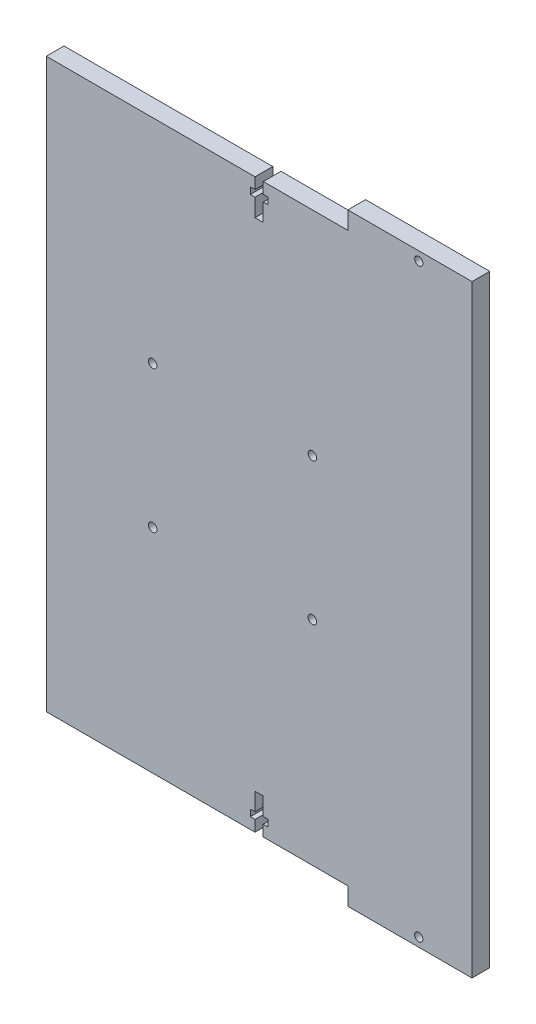
SolidWorks part; units mm, degrees
material "Acrylic (Medium-high impact)"
ref_plane "Front" through (0, 0, 0) normal (0, 0, 1) x (1, 0, 0)
ref_plane "Top" through (0, 0, 0) normal (0, 1, 0) x (1, 0, 0)
ref_plane "Right" through (0, 0, 0) normal (1, 0, 0) x (0, 0, -1)
sketch "Sketch1" plane through (0, 0, 0) normal (0, 0, 1) x (1, 0, 0)
  line L0 (107.95, 215.9) -> (107.95, 209.55)
  line L1 (107.95, 0) -> (152.4, 0)
  line L2 (0, 6.35) -> (0, 209.55)
  line L3 (107.95, 215.9) -> (152.4, 215.9)
  line L4 (152.4, 0) -> (152.4, 215.9)
  line L5 (107.95, 209.55) -> (0, 209.55)
  line L7 (107.95, 0) -> (107.95, 6.35)
  line L8 (107.95, 6.35) -> (0, 6.35)
  dimension "D1" = 152.4
extrude "Boss-Extrude1" add sketch "Sketch1" along normal blind 6.35
sketch "Sketch2" plane through (0, 0, 6.35) normal (0, 0, 1) x (1, 0, 0)
  line L0 (152.4, 215.9) -> (107.95, 215.9) construction
  line L1 (133.35, 184.15) -> (133.35, -24.874) construction
  line L2 (152.4, 0) -> (152.4, 215.9) construction
  line L3 (139.0772, 212.725) -> (-50.8887, 212.725) construction
  line L5 (0, 209.55) -> (0, 6.35) construction
  line L9 (0, 107.95) -> (152.4, 107.95) construction
  line L10 (130.175, 215.9) -> (130.175, 9.0135) construction
  circle A1 centre (133.35, 212.725) radius 1.4732
  circle A2 centre (133.35, 3.175) radius 1.4732
  point P0 (133.35, 212.725)
  point P1 (133.35, 3.175)
  point P22 (130.175, 215.9)
  point P26 (0, 107.95)
  dimension "D2" = 2.9464
  dimension "D1" = 3.175
  dimension "D3" = 19.05
extrude "Cut-Extrude1" cut sketch "Sketch2" against normal through all contours A1
sketch "Sketch4" plane through (0, 0, 6.35) normal (0, 0, 1) x (1, 0, 0)
  line L0 (0, 107.95) -> (183.2199, 107.95) construction
  line L1 (152.4, 0) -> (152.4, 215.9) construction
  line L2 (130.175, 215.9) -> (130.175, 6.5627) construction
  line L4 (0, 209.55) -> (0, 6.35) construction
  line L5 (152.4, 215.9) -> (107.95, 215.9) construction
  circle A1 centre (95.25, 133.35) radius 1.524
  circle A3 centre (95.25, 82.55) radius 1.524
  point P6 (0, 107.95)
  point P11 (130.175, 215.9)
  dimension "D1" = 3.048
  dimension "D2" = 57.15
  dimension "D3" = 82.55
extrude "Cut-Extrude2" cut sketch "Sketch4" against normal through all
sketch "Sketch5" plane through (0, 0, 6.35) normal (0, 0, 1) x (1, 0, 0)
  line L0 (0, 107.95) -> (188.4381, 107.95) construction
  line L2 (0, 209.55) -> (0, 6.35) construction
  line L3 (152.4, 215.9) -> (107.95, 215.9) construction
  circle A0 centre (38.1, 133.35) radius 1.524
  circle A1 centre (38.1, 82.55) radius 1.524
  point P3 (0, 107.95)
  dimension "D1" = 3.048
  dimension "D2" = 38.1
  dimension "D3" = 82.55
extrude "Cut-Extrude3" cut sketch "Sketch5" against normal through all
sketch "Sketch10" plane through (0, 0, 0) normal (0, 0, -1) x (-1, 0, 0)
  line L0 (-50.8, 6.35) -> (-101.6, 6.35) construction
  line L1 (-77.6732, 6.35) -> (-74.7268, 6.35)
  line L2 (-77.6732, 6.35) -> (-77.6732, 10.3188)
  line L3 (-77.6732, 19.05) -> (-74.7268, 19.05)
  line L4 (-74.7268, 6.35) -> (-74.7268, 10.3188)
  line L5 (-79.375, 10.3188) -> (-77.6732, 10.3188)
  line L6 (-79.375, 10.3188) -> (-79.375, 12.7)
  line L7 (-79.375, 12.7) -> (-77.6732, 12.7)
  line L8 (-73.025, 10.3188) -> (-73.025, 12.7)
  line L9 (-77.6732, 6.35) -> (-77.6732, 0) construction
  line L10 (-77.6732, 12.7) -> (-77.6732, 19.05)
  line L11 (-74.7268, 0) -> (-74.7268, 6.35) construction
  line L12 (-74.7268, 12.7) -> (-73.025, 12.7)
  line L13 (-74.7268, 12.7) -> (-74.7268, 19.05)
  line L14 (-74.7268, 10.3188) -> (-73.025, 10.3188)
  line L15 (-2.7493, 107.95) -> (0, 107.95) construction
  line L17 (-152.4, 0) -> (-152.4, 215.9) construction
  line L18 (-73.025, 205.5812) -> (-73.025, 203.2)
  line L19 (-74.7268, 205.5812) -> (-73.025, 205.5812)
  line L20 (-74.7268, 203.2) -> (-73.025, 203.2)
  line L21 (-74.7268, 203.2) -> (-74.7268, 196.85)
  line L22 (-77.6732, 196.85) -> (-74.7268, 196.85)
  line L23 (-77.6732, 203.2) -> (-77.6732, 196.85)
  line L24 (-79.375, 203.2) -> (-77.6732, 203.2)
  line L25 (-79.375, 205.5812) -> (-77.6732, 205.5812)
  line L26 (-79.375, 205.5812) -> (-79.375, 203.2)
  line L27 (-77.6732, 209.55) -> (-74.7268, 209.55)
  line L28 (-77.6732, 209.55) -> (-77.6732, 205.5812)
  line L29 (-74.7268, 209.55) -> (-74.7268, 205.5812)
  point P23 (-152.4, 107.95)
  dimension "D1" = 12.7
  dimension "D2" = 6.35
  dimension "D3" = 2.3813
  dimension "D4" = 6.35
extrude "Cut-Extrude10" cut sketch "Sketch10" against normal through all
